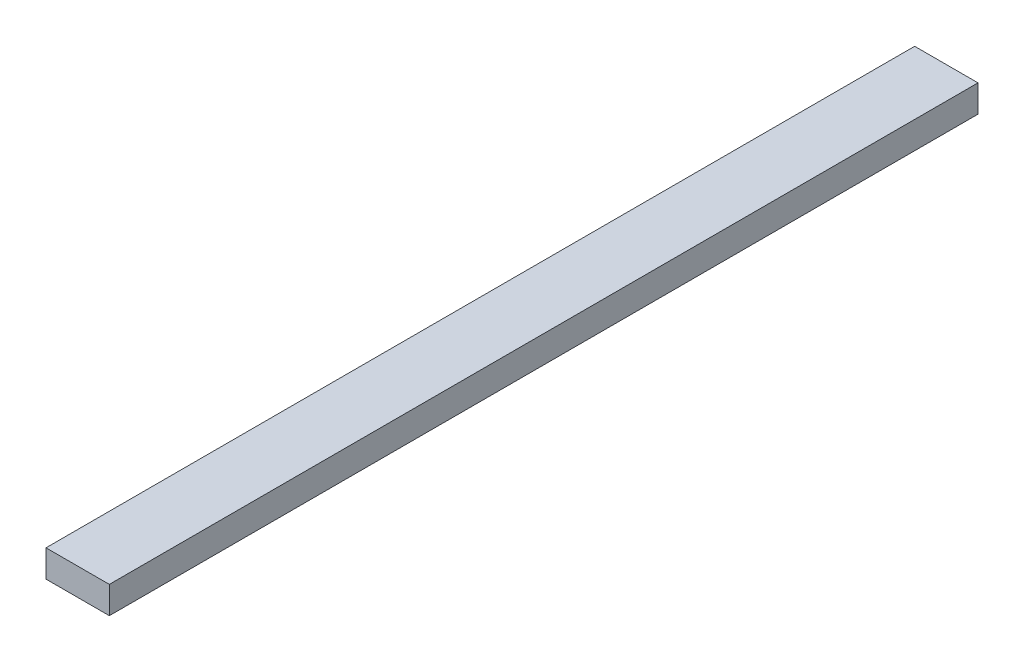
SolidWorks part; units mm, degrees
material "Pine"
ref_plane "Front Plane" through (0, 0, 0) normal (0, 0, 1) x (1, 0, 0)
ref_plane "Top Plane" through (0, 0, 0) normal (0, 1, 0) x (1, 0, 0)
ref_plane "Right Plane" through (0, 0, 0) normal (1, 0, 0) x (0, 0, -1)
sketch "Sketch1" plane through (0, 0, 0) normal (0, 0, 1) x (1, 0, 0)
  line L1 (0, 0) -> (88.9, 0)
  line L2 (0, 0) -> (0, 38.1)
  line L3 (0, 38.1) -> (88.9, 38.1)
  line L4 (88.9, 0) -> (88.9, 38.1)
  dimension "D1" = 88.9
  dimension "D2" = 38.1
extrude "Boss-Extrude1" add sketch "Sketch1" along normal blind 1219.2
sketch "Sketch2" plane through (0, 0, 0) normal (0, 0, -1) x (-1, 0, 0)
  line L1 (-88.9, 0) -> (-88.9, 38.1) construction
  line L2 (0, 38.1) -> (0, 0) construction
  line L3 (-44.45, 19.05) -> (-88.9, 19.05) construction
  line L4 (-44.45, 19.05) -> (0, 19.05) construction
  circle A0 centre (-66.675, 19.05) radius 0.8763
  circle A1 centre (-22.225, 19.05) radius 0.8763
  dimension "D1" = 1.7526
sketch "Sketch3" plane through (0, 0, 0) normal (0, -1, 0) x (1, 0, 0)
  line L0 (44.45, 1219.2) -> (44.45, 1174.75) construction
  line L1 (0, 1219.2) -> (88.9, 1219.2) construction
  line L2 (44.45, 1174.75) -> (44.45, 1130.3) construction
  line L3 (88.9, 609.6) -> (0, 609.6) construction
  line L4 (88.9, 1219.2) -> (88.9, 0) construction
  line L5 (0, 1219.2) -> (0, 0) construction
  line L6 (44.45, 609.6) -> (44.45, 654.05) construction
  line L7 (44.45, 609.6) -> (44.45, 565.15) construction
  circle A0 centre (44.45, 1196.975) radius 0.8763
  circle A1 centre (44.45, 1152.525) radius 0.8763
  circle A2 centre (44.45, 22.225) radius 0.8763
  circle A3 centre (44.45, 66.675) radius 0.8763
  circle A4 centre (44.45, 587.375) radius 0.8763
  circle A5 centre (44.45, 631.825) radius 0.8763
  dimension "D2" = 1.7526
  dimension "D4" = 1.7526
  dimension "D1" = 88.9
  dimension "D3" = 88.9
equation "\"length\"= 20"
equation "\"D1@Boss-Extrude1\" = \"length\""
equation "\"length\"= 22"
equation "\"length\"= 36"
equation "\"length\"= 26"
equation "\"length\"= 27"
equation "\"length\"= 28"
equation "\"length\"= 39"
equation "\"length\"= 48"
